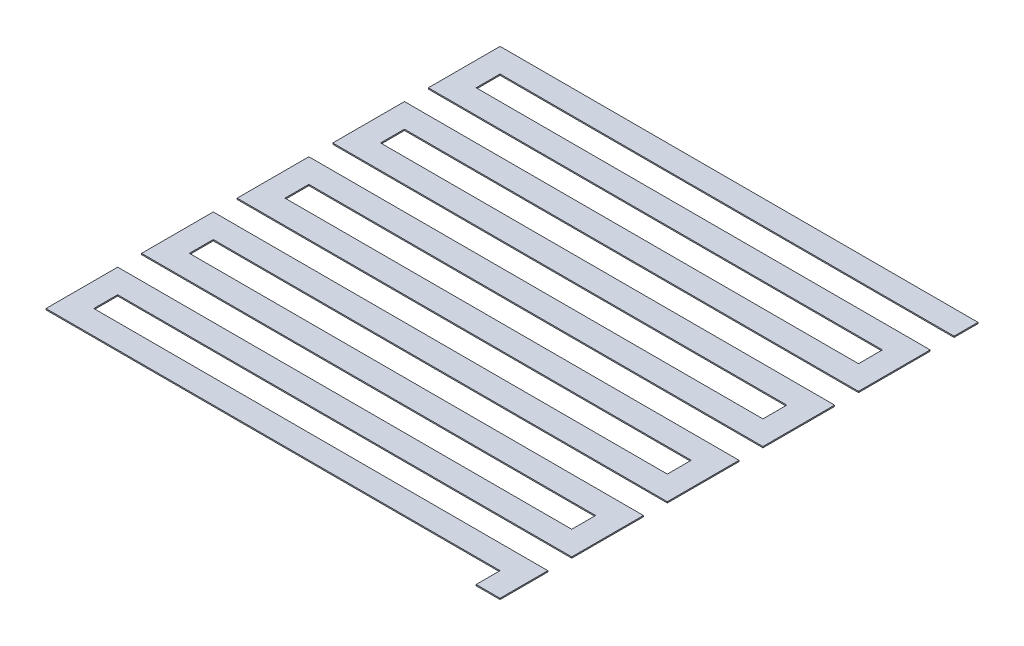
SolidWorks part; units mm, degrees
ref_plane "Front Plane" through (0, 0, 0) normal (0, 0, 1) x (1, 0, 0)
ref_plane "Top Plane" through (0, 0, 0) normal (0, 1, 0) x (1, 0, 0)
ref_plane "Right Plane" through (0, 0, 0) normal (1, 0, 0) x (0, 0, -1)
sketch "Mirror axis y" plane through (0, 0, 0) normal (0, 1, 0) x (1, 0, 0)
  line L0 (0, 10) -> (0, -10)
  point P2 (0, 0)
  point P3 (0, 0)
  point P4 (0, 0)
  point P5 (0, 0)
  point P7 (0, 0)
  dimension "D1" = 20
sketch "Base D" plane through (0, 0, 0) normal (0, 1, 0) x (1, 0, 0)
  line L0 (-10, 10) -> (10, -10) construction
  line L1 (-10, 10) -> (10, 10)
  line L2 (-10, 10) -> (-10, -10)
  line L3 (-10, -10) -> (10, -10)
  line L4 (10, 10) -> (10, -10)
  point P4 (0, 0)
  point P5 (0, 0)
  point P6 (4.7707, 4.8979)
  point P7 (0, 0)
  dimension "D1" = 20
sketch "cutR" plane through (0, 0, 0) normal (0, 1, 0) x (1, 0, 0)
  line L0 (10, 10) -> (10, -10) construction
  line L1 (10, 9) -> (-9, 9)
  line L2 (10, 9) -> (10, 8)
  line L3 (10, 8) -> (-9, 8)
  line L4 (-9, 9) -> (-9, 8)
  line L5 (-10, 10) -> (10, 10) construction
  line L6 (-10, 10) -> (-10, -10) construction
  dimension "D1" = 1
  dimension "D2" = 1
  dimension "D3" = 1
sketch "cutL" plane through (0, 0, 0) normal (0, 1, 0) x (1, 0, 0)
  line L0 (-10, 10) -> (-10, -10) construction
  line L1 (-10, 7) -> (9, 7)
  line L2 (-10, 7) -> (-10, 6)
  line L3 (-10, 6) -> (9, 6)
  line L4 (9, 7) -> (9, 6)
  line L5 (10, 8) -> (-9, 8) construction
  line L6 (10, 10) -> (10, -10) construction
  dimension "D1" = 1
  dimension "D2" = 1
  dimension "D3" = 1
extrude "Boss-Extrude1" add sketch "Base D" along normal blind 0.05
extrude "CutRight" cut sketch "cutR" along normal through all
extrude "CutLeft" cut sketch "cutL" along normal through all
pattern_linear "Patt Right" count 5 spacing 4 along (0, 0, 1) of "CutRight"
pattern_linear "Patt Left" count 5 spacing 4 along (0, 0, 1) of "CutLeft"
